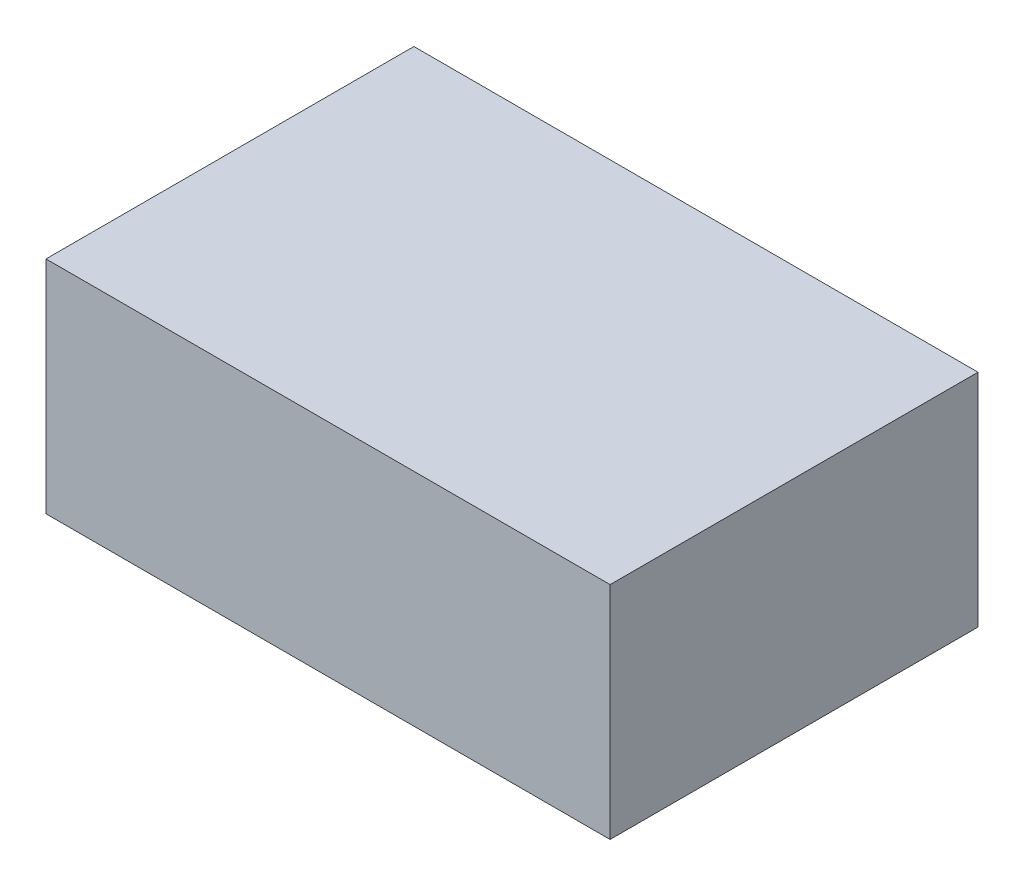
SolidWorks part; units mm, degrees
ref_plane "Front Plane" through (0, 0, 0) normal (0, 0, 1) x (1, 0, 0)
ref_plane "Top Plane" through (0, 0, 0) normal (0, 1, 0) x (1, 0, 0)
ref_plane "Right Plane" through (0, 0, 0) normal (1, 0, 0) x (0, 0, -1)
sketch "Sketch1" plane through (0, 0, 0) normal (0, 1, 0) x (1, 0, 0)
  line L1 (-51.507, 27.0493) -> (63.493, 27.0493)
  line L2 (-51.507, 27.0493) -> (-51.507, -47.9507)
  line L3 (-51.507, -47.9507) -> (63.493, -47.9507)
  line L4 (63.493, 27.0493) -> (63.493, -47.9507)
  dimension "D1" = 115
  dimension "D2" = 75
extrude "Boss-Extrude2" add sketch "Sketch1" along normal blind 45
